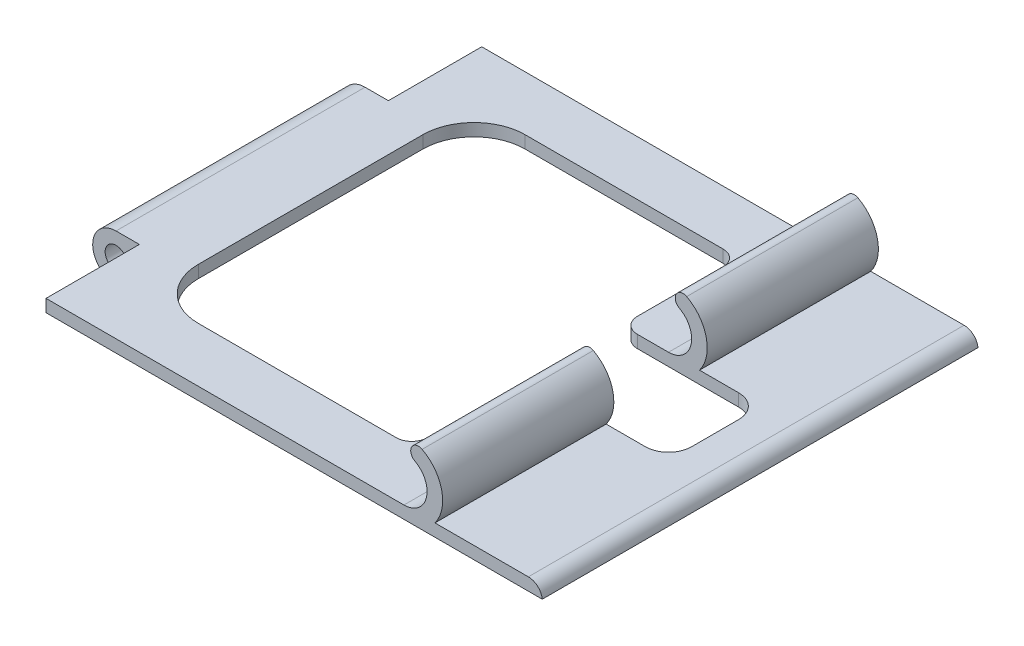
SolidWorks part; units mm, degrees
ref_plane "前视基准面" through (0, 0, 0) normal (0, 0, 1) x (1, 0, 0)
ref_plane "上视基准面" through (0, 0, 0) normal (0, 1, 0) x (1, 0, 0)
ref_plane "右视基准面" through (0, 0, 0) normal (1, 0, 0) x (0, 0, -1)
other "Configuration Table"
sketch "草图1" plane through (0, 0, 0) normal (0, 0, 1) x (1, 0, 0)
  line L2 (154.9687, 4) -> (124.9687, 4)
  line L3 (115, 4) -> (0, 4)
  line L5 (0, 4) -> (-7.5, 4)
  line L6 (1142.4687, 2.5) -> (141.8616, 2.5) construction
  line L7 (115, 4) -> (115, 0) construction
  line L8 (115, 0) -> (159.4404, 0)
  line L9 (0, 0) -> (115, 0)
  line L11 (-0.8668, 0) -> (0, 0)
  line L12 (0, 4) -> (0, -12.9606) construction
  arc A1 (115, 4) -> (118.5, 18) centre (115, 11.4375) ccw
  arc A2 (124.9687, 4) -> (120.8529, 22.4118) centre (115, 11.4375) ccw
  arc A3 (118.5, 18) -> (120.8529, 22.4118) centre (119.6765, 20.2059) cw
  arc A4 (115, -1) -> (120.8529, 22.4118) centre (115, 11.4375) ccw construction
  arc A6 (154.9687, 4) -> (159.4404, 0) centre (154.9687, -0.4995) cw
  arc A8 (-7.5, 4) -> (-0.8668, 0) centre (-7.5, -3.5) ccw
  circle A9 centre (-7.5, -3.5) radius 3.5
  point P6 (0, 0)
  point P17 (138.5318, 0.4131)
  point P22 (139.3578, -0.408)
  point P23 (0, 0)
  point P26 (0, 0)
  point P27 (139.4404, 0)
  dimension "D3" = 7
  dimension "D4" = 4
  dimension "D2" = 30
  dimension "D5" = 115
  dimension "D6" = 4
  dimension "D7" = 14
  dimension "D8" = 3.5
  dimension "D1" = 5
extrude "凸台-拉伸1" add sketch "草图1" against normal blind 140
ref_plane "基准面1" through (0, 0, 0) normal (1, 0, 0) x (0, 0, -1)
sketch "草图2" plane through (0, 0, 0) normal (1, 0, 0) x (0, 0, -1)
  line L4 (0, 11.5) -> (0, -15.8449)
  line L5 (0, -15.8449) -> (30, -15.8449)
  line L6 (30, -15.8449) -> (30, 11.5)
  line L7 (30, 11.5) -> (0, 11.5)
  line L8 (70, 11.5) -> (70, -6.5) construction
  line L9 (110, -15.8449) -> (110, 11.5)
  line L10 (140, -15.8449) -> (110, -15.8449)
  line L11 (140, 11.5) -> (140, -15.8449)
  line L12 (110, 11.5) -> (140, 11.5)
  dimension "D1" = 30
extrude "切除-拉伸1" cut sketch "草图2" against normal through all
sketch "草图3" plane through (0, 4, 0) normal (0, 1, 0) x (1, 0, 0)
  line L0 (115, 140) -> (115, 0) construction
  line L1 (15, 17.5) -> (115, 17.5) construction
  line L2 (15, 17.5) -> (15, 122.5) construction
  line L3 (15, 122.5) -> (115, 122.5) construction
  line L4 (115, 17.5) -> (115, 122.5) construction
  line L5 (65, 122.5) -> (65, 140) construction
  line L6 (115, 140) -> (0, 140) construction
  line L7 (65, 17.5) -> (65, 0) construction
  line L8 (115, 0) -> (0, 0) construction
  line L9 (115, 85) -> (145, 85) construction
  line L10 (145, 85) -> (145, 55) construction
  line L11 (145, 55) -> (115, 55) construction
  line L12 (115, 122.5) -> (115, 85) construction
  line L13 (115, 55) -> (115, 17.5) construction
  line L14 (31.4428, 122.5) -> (31.4428, 17.5) construction
  line L15 (137.5718, 85) -> (137.5718, 55) construction
  line L16 (15, 106.0572) -> (15, 33.9428)
  line L17 (31.4428, 122.5) -> (115, 122.5) construction
  line L18 (31.4428, 17.5) -> (115, 17.5) construction
  line L19 (115, 85) -> (137.5718, 85)
  line L20 (145, 77.5718) -> (145, 62.4282)
  line L21 (137.5718, 55) -> (115, 55)
  line L22 (100, 117.5599) -> (100, 90)
  line L23 (105, 85) -> (115, 85)
  line L24 (31.4428, 122.5) -> (95.0599, 122.5)
  line L25 (15, 70) -> (115, 70) construction
  line L26 (105, 55) -> (115, 55)
  line L27 (31.4428, 17.5) -> (95.0599, 17.5)
  line L28 (100, 22.4401) -> (100, 50)
  arc A0 (31.4428, 122.5) -> (15, 106.0572) centre (31.4428, 106.0572) ccw
  arc A1 (15, 33.9428) -> (31.4428, 17.5) centre (31.4428, 33.9428) ccw
  arc A2 (145, 62.4282) -> (137.5718, 55) centre (137.5718, 62.4282) cw
  arc A3 (137.5718, 85) -> (145, 77.5718) centre (137.5718, 77.5718) cw
  arc A4 (100, 90) -> (105, 85) centre (105, 90) ccw
  arc A5 (95.0599, 122.5) -> (100, 117.5599) centre (95.0599, 117.5599) cw
  arc A6 (95.0599, 17.5) -> (100, 22.4401) centre (95.0599, 22.4401) ccw
  arc A7 (100, 50) -> (105, 55) centre (105, 50) cw
  dimension "D1" = 105
  dimension "D2" = 100
  dimension "D3" = 30
  dimension "D4" = 30
  dimension "D5" = 15
  dimension "D6" = 10
extrude "切除-拉伸3" cut sketch "草图3" against normal through all and the other way through all
